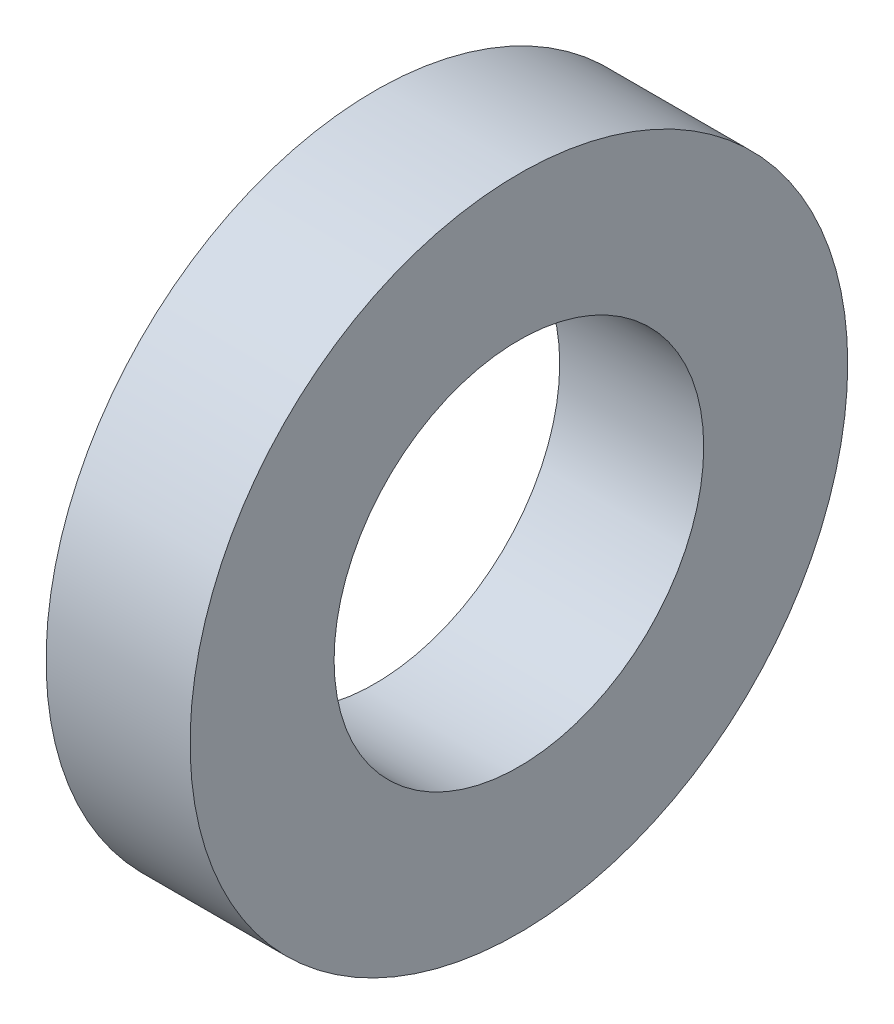
SolidWorks part; units mm, degrees
ref_plane "Front Plane" through (0, 0, 0) normal (0, 0, 1) x (1, 0, 0)
ref_plane "Top Plane" through (0, 0, 0) normal (0, 1, 0) x (1, 0, 0)
ref_plane "Right Plane" through (0, 0, 0) normal (1, 0, 0) x (0, 0, -1)
sketch "Sketch1" plane through (0, 0, 0) normal (1, 0, 0) x (0, 0, -1)
  circle A0 centre (0, 0) radius 14.5
  circle A1 centre (0, 0) radius 8.15
  dimension "D1" = 29
  dimension "D2" = 6.35
extrude "Boss-Extrude1" add sketch "Sketch1" along normal blind 6.35
